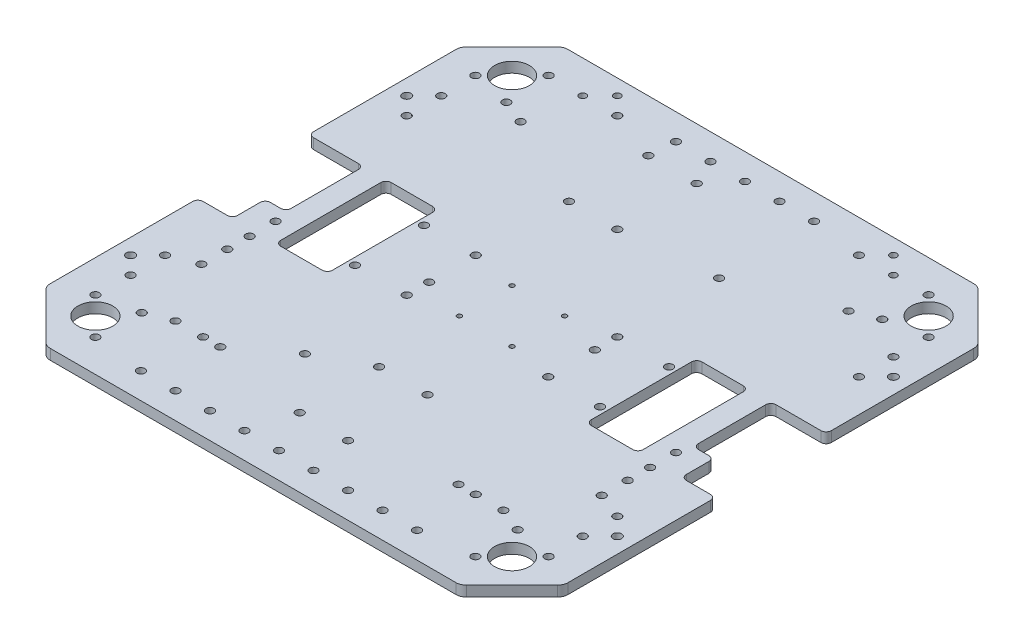
SolidWorks part; units mm, degrees
ref_plane "Plan de face" through (0, 0, 0) normal (0, 0, 1) x (1, 0, 0)
ref_plane "Plan de dessus" through (0, 0, 0) normal (0, 1, 0) x (1, 0, 0)
ref_plane "Plan de droite" through (0, 0, 0) normal (1, 0, 0) x (0, 0, -1)
sketch "Esquisse1" plane through (0, 0, 0) normal (0, 1, 0) x (1, 0, 0)
  line L0 (150, -150) -> (150, 150) construction
  line L1 (150, 150) -> (0, 150) construction
  line L2 (-150, 150) -> (-150, -150) construction
  line L3 (-150, 150) -> (150, 150) construction
  line L4 (150, 0) -> (-150, 0) construction
  line L5 (150, -150) -> (-150, -150) construction
  line L6 (0, 150) -> (0, -150) construction
  line L7 (-150, 0) -> (-150, 120)
  line L8 (0, 150) -> (-120, 150)
  line L9 (-150, 120) -> (-120, 150)
  line L10 (0, 150) -> (120, 150)
  line L11 (150, 0) -> (150, 120)
  line L12 (150, 120) -> (120, 150)
  line L13 (-150, 0) -> (-150, -120)
  line L14 (0, -150) -> (-120, -150)
  line L15 (-120, -150) -> (-150, -120)
  line L16 (150, 0) -> (150, -120)
  line L17 (0, -150) -> (120, -150)
  line L18 (120, -150) -> (150, -120)
  dimension "D1" = 42.4264
  dimension "D2" = 240
  dimension "D3" = 120
  dimension "D4" = 42.4264
  dimension "D5" = 120
  dimension "D6" = 300
  dimension "D7" = 300
  dimension "D8" = 30
extrude "Boss.-Extru.1" add sketch "Esquisse1" along normal blind 6
sketch "Esquisse2" plane through (0, 6, 0) normal (0, 1, 0) x (1, 0, 0)
  line L0 (-150, 0) -> (150, 0) construction
  line L1 (-150, 120) -> (-150, -120) construction
  line L2 (150, -120) -> (150, 120) construction
  line L3 (0, -150) -> (0, 150) construction
  line L4 (-120, -150) -> (120, -150) construction
  line L5 (120, 150) -> (-120, 150) construction
  line L6 (-150, 120) -> (-120, 150) construction
  line L7 (-120, 150) -> (-105.6975, 135.6975) construction
  line L8 (-105.6975, 135.6975) -> (-135.6975, 105.6975) construction
  line L9 (-135.6975, 105.6975) -> (-150, 120) construction
  line L10 (-120.6975, 120.6975) -> (-110.0909, 131.3041) construction
  line L11 (-120.6975, 120.6975) -> (-131.3041, 110.0909) construction
  line L12 (-135, -135) -> (135, 135) construction
  line L13 (-150, -120) -> (-120, -150) construction
  line L14 (150, 120) -> (120, 150) construction
  line L15 (-120.6975, 120.6975) -> (0, 120.6975) construction
  circle A0 centre (-120.6975, 120.6975) radius 10.1
  circle A1 centre (-131.3041, 110.0909) radius 2.3
  circle A2 centre (-110.0909, 131.3041) radius 2.3
extrude "Enlèv. mat.-Extru.1" cut sketch "Esquisse2" against normal up to next
mirror "Symétrie1" about plane through (0, 0, 0) normal (1, 0, 0) of "Enlèv. mat.-Extru.1"
mirror "Symétrie2" about plane through (0, 0, 0) normal (0, 0, 1) of "Symétrie1", "Enlèv. mat.-Extru.1"
sketch "Esquisse3" plane through (0, 6, 0) normal (0, 1, 0) x (1, 0, 0)
  line L0 (-150, 0) -> (150, 0) construction
  line L1 (-150, 120) -> (-150, -120) construction
  line L2 (150, -120) -> (150, 120) construction
  line L3 (0, -150) -> (0, 150) construction
  line L4 (-120, -150) -> (120, -150) construction
  line L5 (120, 150) -> (-120, 150) construction
  line L6 (-150, 0) -> (-150, -32)
  line L7 (-150, -32) -> (-130, -32)
  line L8 (-130, -32) -> (-130, 32)
  line L9 (-130, 32) -> (-150, 32)
  line L10 (-150, 32) -> (-150, 0)
extrude "Enlèv. mat.-Extru.2" cut sketch "Esquisse3" against normal up to next and the other way through all
mirror "Symétrie3" about plane through (0, 0, 0) normal (1, 0, 0) of "Enlèv. mat.-Extru.2"
fillet "Congé1" radius 3 8 edges at (150, 3, 32) (150, 3, -32) (130, 3, -32) (130, 3, 32) (-150, 3, -32) (-150, 3, 32) (-130, 3, 32) (-130, 3, -32)
sketch "Esquisse4" plane through (0, 6, 0) normal (0, 1, 0) x (1, 0, 0)
  line L0 (0, -150) -> (0, 150) construction
  line L1 (-120, -150) -> (120, -150) construction
  line L2 (120, 150) -> (-120, 150) construction
  line L3 (0, 150) -> (0, 0) construction
  line L4 (0, 0) -> (-130, 0) construction
  line L5 (-130, -29) -> (-130, 29) construction
  line L6 (-130, 0) -> (-105, 0) construction
  line L7 (-105, 0) -> (-105, 32)
  line L8 (-105, 32) -> (-75, 32)
  line L9 (-75, 32) -> (-75, -32)
  line L10 (-75, -32) -> (-105, -32)
  line L11 (-105, -32) -> (-105, 0)
extrude "Enlèv. mat.-Extru.3" cut sketch "Esquisse4" against normal up to next
mirror "Symétrie4" about plane through (0, 0, 0) normal (1, 0, 0) of "Enlèv. mat.-Extru.3"
fillet "Congé2" radius 3 8 edges at (105, 3, -32) (75, 3, -32) (75, 3, 32) (105, 3, 32) (-105, 3, 32) (-75, 3, 32) (-75, 3, -32) (-105, 3, -32)
sketch "Esquisse5" plane through (0, 6, 0) normal (0, 1, 0) x (1, 0, 0)
  line L0 (-75, 0) -> (-67, 0) construction
  line L1 (-75, -29) -> (-75, 29) construction
  line L2 (-67, 0) -> (-67, 24) construction
  line L3 (-67, 0) -> (-67, -24) construction
  line L4 (-67, -24) -> (-75, -24) construction
  line L5 (-75, -24) -> (-75, -16) construction
  line L6 (-75, -16) -> (-67, -24) construction
  line L7 (-67, -24) -> (-75, -24) construction
  line L9 (-67, 24) -> (-75, 24) construction
  line L10 (-75, 24) -> (-75, 16) construction
  line L11 (-75, 16) -> (-67, 24) construction
  line L12 (-67, 24) -> (-75, 24) construction
  circle A0 centre (-71, 20) radius 2.3
  circle A1 centre (-71, -20) radius 2.3
extrude "Enlèv. mat.-Extru.4" cut sketch "Esquisse5" against normal up to next
mirror "Symétrie5" about plane through (0, 0, 0) normal (1, 0, 0) of "Enlèv. mat.-Extru.4"
sketch "Esquisse6" plane through (0, 6, 0) normal (0, 1, 0) x (1, 0, 0)
  line L0 (-75, 0) -> (-75, 24) construction
  line L1 (-75, -29) -> (-75, 29) construction
  line L2 (-75, 24) -> (-67, 24) construction
  line L3 (-67, 24) -> (-45, 24) construction
  line L4 (-45, 24) -> (-37, 24) construction
  line L5 (-37, 24) -> (-37, -24) construction
  line L6 (-37, -24) -> (-45, -24) construction
  line L7 (-45, 24) -> (-45, 16) construction
  line L8 (-45, 16) -> (-37, 24) construction
  line L9 (-45, -24) -> (-45, -16) construction
  line L10 (-45, -16) -> (-37, -24) construction
  line L11 (-37, 24) -> (-37, -83) construction
  line L12 (-37, -83) -> (-45, -83) construction
  line L13 (-45, -83) -> (-45, -75) construction
  line L14 (-45, -75) -> (-37, -83) construction
  line L15 (75, 0) -> (67, 0) construction
  line L16 (75, -29) -> (75, 29) construction
  line L17 (75, 0) -> (75, -24) construction
  line L18 (75, -24) -> (67, -24) construction
  line L19 (67, 24) -> (75, 24) construction
  line L20 (75, 24) -> (75, 0) construction
  line L21 (67, -24) -> (45, -24) construction
  line L22 (45, -24) -> (45, -16) construction
  line L23 (67, -24) -> (67, 0) construction
  line L24 (45, -16) -> (37, -16) construction
  line L25 (37, -16) -> (37, -24) construction
  line L26 (37, -24) -> (45, -24) construction
  line L27 (45, -24) -> (37, -16) construction
  line L28 (37, -24) -> (37, 83) construction
  line L29 (37, 83) -> (45, 83) construction
  line L30 (45, 83) -> (45, 75) construction
  line L31 (45, 75) -> (37, 83) construction
  line L32 (37, 24) -> (45, 24) construction
  line L33 (45, 24) -> (45, 16) construction
  line L34 (45, 16) -> (37, 24) construction
  line L35 (37, -16) -> (37, 3) construction
  line L36 (37, 3) -> (45, 3) construction
  line L37 (45, 3) -> (45, 11) construction
  line L38 (45, 11) -> (37, 3) construction
  line L39 (-37, 24) -> (-37, -3) construction
  line L40 (-37, -3) -> (-45, -3) construction
  line L41 (-45, -3) -> (-45, -11) construction
  line L42 (-45, -11) -> (-37, -3) construction
  circle A0 centre (-41, -79) radius 2.3
  circle A1 centre (-41, -20) radius 2.3
  circle A2 centre (-41, 20) radius 2.3
  circle A3 centre (41, -20) radius 2.3
  circle A4 centre (41, 79) radius 2.3
  circle A5 centre (41, 20) radius 2.3
  circle A6 centre (41, 7) radius 2.3
  circle A7 centre (-41, -7) radius 2.3
extrude "Enlèv. mat.-Extru.5" cut sketch "Esquisse6" against normal up to next
sketch "Esquisse7" plane through (0, 6, 0) normal (0, 1, 0) x (1, 0, 0)
  line L1 (-3.3, 0) -> (3.3, 0) construction
  line L2 (150, -120) -> (150, -35) construction
  line L3 (120, -150) -> (150, -120) construction
  line L4 (131, 80) -> (131, 90) construction
  line L5 (131, 80) -> (131, 70) construction
  line L7 (150, -120) -> (150, -80) construction
  line L8 (150, -80) -> (146, -80) construction
  line L9 (146, -80) -> (141, -80) construction
  line L10 (141, -80) -> (131, -80) construction
  line L11 (131, -80) -> (131, -70) construction
  line L12 (131, -80) -> (131, -90) construction
  line L13 (141, 80) -> (131, 80) construction
  line L14 (146, 80) -> (141, 80) construction
  circle A9 centre (141, -80) radius 2.4769
  circle A10 centre (131, -90) radius 2.3
  circle A11 centre (131, -70) radius 2.3
  circle A12 centre (131, 70) radius 2.3
  circle A13 centre (131, 90) radius 2.3
  circle A14 centre (141, 80) radius 2.4769
  dimension "D1" = 40
  dimension "D2" = 4
  dimension "D3" = 5
extrude "Enlèv. mat.-Extru.6" cut sketch "Esquisse7" against normal up to next
mirror "Symétrie6" about plane through (0, 0, 0) normal (1, 0, 0) of "Enlèv. mat.-Extru.6"
sketch "Esquisse8" plane through (0, 6, 0) normal (0, 1, 0) x (1, 0, 0)
  line L0 (-60, -150) -> (-60, -135) construction
  line L1 (-40, -150) -> (-40, -135) construction
  line L2 (-20, -150) -> (-20, -135) construction
  line L3 (-120, -150) -> (-80, -150) construction
  line L4 (-80, -150) -> (-80, -135) construction
  line L5 (120, -150) -> (80, -150) construction
  line L6 (80, -150) -> (80, -135) construction
  line L7 (0, -150) -> (0, -135) construction
  line L8 (20, -150) -> (20, -135) construction
  line L9 (40, -150) -> (40, -135) construction
  line L10 (60, -150) -> (60, -135) construction
  line L11 (-3.3, 0) -> (3.3, 0) construction
  line L12 (40, 150) -> (40, 135) construction
  line L13 (20, 150) -> (20, 135) construction
  line L14 (0, 150) -> (0, 135) construction
  line L15 (-20, 150) -> (-20, 135) construction
  line L16 (-40, 150) -> (-40, 135) construction
  circle A0 centre (-80, -135) radius 2.3
  circle A1 centre (80, -135) radius 2.3
  circle A2 centre (-60, -135) radius 2.3
  circle A3 centre (-40, -135) radius 2.3
  circle A4 centre (-20, -135) radius 2.3
  circle A5 centre (0, -135) radius 2.3
  circle A6 centre (20, -135) radius 2.3
  circle A7 centre (40, -135) radius 2.3
  circle A8 centre (60, -135) radius 2.3
  circle A9 centre (40, 135) radius 2.3
  circle A10 centre (20, 135) radius 2.3
  circle A11 centre (0, 135) radius 2.3
  circle A12 centre (-20, 135) radius 2.3
  circle A13 centre (-40, 135) radius 2.3
  dimension "D1" = 8
extrude "Enlèv. mat.-Extru.7" cut sketch "Esquisse8" against normal up to next
sketch "Esquisse10" plane through (0, 6, 0) normal (0, 1, 0) x (1, 0, 0)
  line L0 (-150, -120) -> (-150, -32) construction
  line L1 (-150, -32) -> (-120, -32) construction
  line L2 (-120, -32) -> (-112, -32) construction
  line L3 (-112, -32) -> (-112, -40) construction
  line L4 (-112, -40) -> (-120, -40) construction
  line L5 (-120, -40) -> (-120, -60) construction
  line L6 (-120, -60) -> (-112, -60) construction
  line L7 (-112, -60) -> (-112, -68) construction
  line L8 (-112, -68) -> (-120, -60) construction
  line L9 (-120, -32) -> (-112, -40) construction
  circle A0 centre (-116, -36) radius 2.3
  circle A1 centre (-116, -64) radius 2.3
extrude "Enlèv. mat.-Extru.8" cut sketch "Esquisse10" against normal up to next
mirror "Symétrie8" about plane through (0, 0, 0) normal (1, 0, 0) of "Enlèv. mat.-Extru.8"
fillet "Congé3" radius 6 8 edges at (-150, 3, -120) (-120, 3, -150) (120, 3, -150) (150, 3, -120) (150, 3, 120) (120, 3, 150) (-120, 3, 150) (-150, 3, 120)
sketch "Esquisse11" plane through (0, 6, 0) normal (0, 1, 0) x (1, 0, 0)
  line L0 (150, 0) -> (-150, 0) construction
  line L1 (-150, 0) -> (-150, -32) construction
  line L2 (-150, -32) -> (-120, -32) construction
  line L3 (-120, -32) -> (-120, -25) construction
  line L4 (-120, -25) -> (-120, -17) construction
  line L5 (-120, -17) -> (-112, -17) construction
  line L6 (-112, -17) -> (-112, -25) construction
  line L7 (-112, -25) -> (-112, -45) construction
  line L8 (-112, -45) -> (-112, -53) construction
  line L9 (-112, -53) -> (-120, -53) construction
  line L10 (-120, -53) -> (-120, -32) construction
  line L11 (-112, -45) -> (-120, -45) construction
  line L12 (-120, -45) -> (-112, -53) construction
  line L13 (-120, -25) -> (-112, -17) construction
  line L14 (0, -3.3) -> (0, 3.3) construction
  line L15 (120, -25) -> (112, -17) construction
  line L16 (120, -45) -> (112, -53) construction
  line L17 (112, -45) -> (120, -45) construction
  line L18 (120, -53) -> (120, -32) construction
  line L19 (112, -53) -> (120, -53) construction
  line L20 (112, -45) -> (112, -53) construction
  line L21 (112, -25) -> (112, -45) construction
  line L22 (112, -17) -> (112, -25) construction
  line L23 (120, -17) -> (112, -17) construction
  line L24 (120, -25) -> (120, -17) construction
  line L25 (120, -32) -> (120, -25) construction
  line L26 (150, -32) -> (120, -32) construction
  line L27 (150, 0) -> (150, -32) construction
  circle A0 centre (-116, -21) radius 2.3
  circle A1 centre (-116, -49) radius 2.3
  circle A2 centre (116, -49) radius 2.3
  circle A3 centre (116, -21) radius 2.3
  point P30 (0, 0)
extrude "Enlèv. mat.-Extru.9" cut sketch "Esquisse11" against normal up to next
sketch "Esquisse12" plane through (0, 6, 0) normal (0, 1, 0) x (1, 0, 0)
  line L0 (0, -3.3) -> (0, 3.3) construction
  line L1 (-108.9078, -105.6191) -> (-97.0876, -114.854) construction
  line L2 (-97.0876, -114.854) -> (-95, -100) construction
  line L3 (95, -100) -> (95, -150) construction
  line L4 (97.0876, -114.854) -> (95, -100) construction
  line L5 (108.9078, -105.6191) -> (97.0876, -114.854) construction
  line L6 (-95, -100) -> (-95, -150) construction
  line L7 (-117.5147, -150) -> (117.5147, -150) construction
  circle A2 centre (-95, -100) radius 2.3
  circle A5 centre (-108.9078, -105.6191) radius 2.3
  circle A15 centre (108.9078, -105.6191) radius 2.3
  circle A16 centre (95, -100) radius 2.3
  point P7 (0, -150)
  dimension "D1" = 95
  dimension "D6" = 60
  dimension "D2" = 50
  dimension "D3" = 15
  dimension "D4" = 50
  dimension "D5" = 15
  dimension "D7" = 8
extrude "Enlèv. mat.-Extru.10" cut sketch "Esquisse12" against normal up to next
mirror "Symétrie9" about plane through (0, 0, 0) normal (0, 0, 1) of "Enlèv. mat.-Extru.10"
sketch "Esquisse13" plane through (0, 6, 0) normal (0, 1, 0) x (1, 0, 0)
  line L0 (74, -150) -> (-74, -150) construction
  line L1 (-117.5147, -150) -> (117.5147, -150) construction
  line L2 (-74, -150) -> (-74, -100) construction
  line L3 (-74, -100) -> (-69, -100) construction
  line L4 (-74, -100) -> (-79, -100) construction
  line L5 (0, -3.3) -> (0, 3.3) construction
  line L6 (74, -100) -> (79, -100) construction
  line L7 (74, -100) -> (69, -100) construction
  line L8 (74, -150) -> (74, -100) construction
  circle A0 centre (-79, -100) radius 2.3
  circle A1 centre (-69, -100) radius 2.3
  circle A2 centre (69, -100) radius 2.3
  circle A3 centre (79, -100) radius 2.3
  point P15 (0, -150)
  dimension "D1" = 74
  dimension "D2" = 50
  dimension "D3" = 5
  dimension "D4" = 5
extrude "Enlèv. mat.-Extru.11" cut sketch "Esquisse13" against normal up to next
sketch "Esquisse14" plane through (0, 6, 0) normal (0, 1, 0) x (1, 0, 0)
  line L0 (0, 150) -> (80, 150) construction
  line L1 (117.5147, 150) -> (-117.5147, 150) construction
  line L2 (80, 150) -> (80, 131) construction
  line L3 (80, 131) -> (70, 131) construction
  line L4 (80, 131) -> (90, 131) construction
  line L5 (80, 150) -> (80, 141) construction
  circle A0 centre (70, 131) radius 2.3
  circle A1 centre (90, 131) radius 2
  circle A2 centre (80, 141) radius 2
  dimension "D2" = 19
  dimension "D4" = 10
  dimension "D1" = 80
  dimension "D3" = 10
  dimension "D5" = 9
extrude "Enlèv. mat.-Extru.12" cut sketch "Esquisse14" against normal up to next
mirror "Symétrie10" about plane through (0, 0, 0) normal (1, 0, 0) of "Enlèv. mat.-Extru.12"
sketch "Esquisse15" plane through (0, 6, 0) normal (0, 1, 0) x (1, 0, 0)
  line L0 (-90, 32) -> (-150, 32) construction
  line L1 (-78, 32) -> (-102, 32) construction
  line L2 (-150, 32) -> (-150, 35) construction
  line L3 (-150, 32) -> (-150, -13) construction
  line L4 (-150, -13) -> (-133, -13) construction
  line L5 (-133, -13) -> (-118, -13)
  line L6 (-118, -13) -> (-118, 32)
  line L7 (-133, -13) -> (-133, 32)
  line L8 (-133, 32) -> (-118, 32)
  dimension "D1" = 17
  dimension "D2" = 45
extrude "Enlèv. mat.-Extru.13" cut sketch "Esquisse15" against normal up to next
mirror "Symétrie11" about plane through (0, 0, 0) normal (1, 0, 0) of "Enlèv. mat.-Extru.13"
fillet "Congé4" radius 3 6 edges at (-118, 3, 13) (-130, 3, 13) (-118, 3, -32) (118, 3, -32) (118, 3, 13) (130, 3, 13)
sketch "Esquisse16" plane through (0, 6, 0) normal (0, 1, 0) x (1, 0, 0)
  line L0 (0, 0) -> (0, -21) construction
  line L1 (0, -21) -> (21, -21) construction
  line L2 (0, 0) -> (0, 21) construction
  line L3 (0, 21) -> (-21, 21) construction
  line L4 (-21, 0) -> (21, 0) construction
  line L5 (-21, 21) -> (21, 21)
  line L6 (-21, 21) -> (-21, -21)
  line L7 (-21, -21) -> (21, -21)
  line L8 (21, 21) -> (21, -21)
  line L9 (-21, -21) -> (-15.25, -21)
  line L10 (-21, -21) -> (-21, -15.25)
  line L11 (-21, -15.25) -> (-15.25, -15.25)
  line L12 (-15.25, -21) -> (-15.25, -15.25)
  line L13 (21, -21) -> (15.25, -21)
  line L14 (21, -21) -> (21, -15.25)
  line L15 (21, -15.25) -> (15.25, -15.25)
  line L16 (15.25, -21) -> (15.25, -15.25)
  circle A0 centre (15.25, -15.25) radius 1.35
  circle A1 centre (-15.25, -15.25) radius 1.35
  circle A2 centre (15.25, 15.25) radius 1.35
  circle A3 centre (-15.25, 15.25) radius 1.35
extrude "Enlèv. mat.-Extru.14" cut sketch "Esquisse16" against normal blind 10 contours A1 | A3 | A2 | A0
sketch "Esquisse17" plane through (0, 6, 0) normal (0, 1, 0) x (1, 0, 0)
  line L0 (-150, -97.6856) -> (-13, -97.6856) construction
  line L1 (-150, -35) -> (-150, -117.5147) construction
  line L2 (-150, -89.4528) -> (15, -89.4528) construction
  line L3 (-13, -150) -> (-13, -110) construction
  line L4 (-117.5147, -150) -> (117.5147, -150) construction
  line L5 (15, -150) -> (15, -110) construction
  line L6 (0, -150) -> (0, -87) construction
  line L7 (0, -87) -> (-48.4176, -87) construction
  line L8 (-150, 98.5082) -> (-41, 98.5082) construction
  line L10 (-150, 117.5147) -> (-150, 35) construction
  line L11 (-41, 150) -> (-41, 120) construction
  line L12 (117.5147, 150) -> (-117.5147, 150) construction
  line L13 (-150, 89.086) -> (-13, 89.086) construction
  line L14 (-13, 150) -> (-13, 120) construction
  line L15 (-27.2714, 150) -> (-27.2714, 97) construction
  line L16 (-27.2714, 97) -> (53.7039, 97) construction
  circle A0 centre (-13, -110) radius 2.3
  circle A1 centre (15, -110) radius 2.3
  circle A2 centre (15, -64) radius 2.3
  circle A3 centre (-13, -64) radius 2.3
  circle A4 centre (-41, 120) radius 2.3
  circle A5 centre (-13, 120) radius 2.3
  circle A6 centre (-13, 74) radius 2.3
  circle A7 centre (-41, 74) radius 2.3
  point P45 (-12.5732, -112.26)
  dimension "D1" = 28
  dimension "D2" = 46
extrude "Enlèv. mat.-Extru.16" cut sketch "Esquisse17" against normal blind 10
